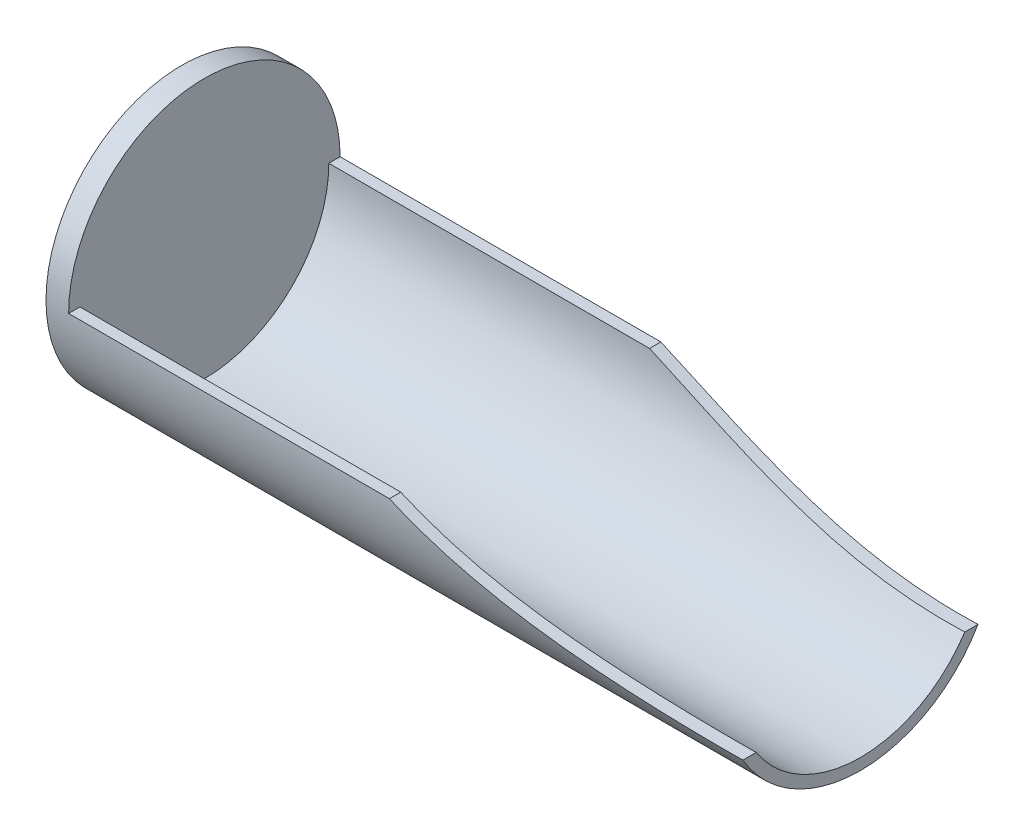
SolidWorks part; units mm, degrees
ref_plane "Front Plane" through (0, 0, 0) normal (0, 0, 1) x (1, 0, 0)
ref_plane "Top Plane" through (0, 0, 0) normal (0, 1, 0) x (1, 0, 0)
ref_plane "Right Plane" through (0, 0, 0) normal (1, 0, 0) x (0, 0, -1)
sketch "Sketch1" plane through (0, 0, 0) normal (1, 0, 0) x (0, 0, -1)
  circle A0 centre (0, 0) radius 120
  dimension "D1" = 240
extrude "Boss-Extrude1" add sketch "Sketch1" along normal blind 600
sketch "Sketch2" plane through (600, 0, 0) normal (1, 0, 0) x (0, 0, -1)
  line L2 (-110, 0) -> (-120, 0)
  line L3 (110, 0) -> (120, 0)
  arc A0 (-110, 0) -> (110, 0) centre (0, 0) ccw
  circle A1 centre (0, 0) radius 120 construction
  arc A2 (120, 0) -> (-120, 0) centre (0, 0) ccw
  dimension "D1" = 110
extrude "Cut-Extrude1" cut sketch "Sketch2" against normal blind 580
sketch "Sketch5" plane through (0, 0, 0) normal (0, 0, 1) x (1, 0, 0)
  line L0 (20, 0) -> (600, 0) construction
  line L1 (600, -120) -> (600, 0) construction
  line L2 (303.5799, 0) -> (600, 0)
  line L3 (600, 0) -> (600, -60)
  spline S0 degree 2 poles (303.5799, 0) (445.5694, -63.3403) (600, -60) knots 0 0 0 1 1 1
extrude "Cut-Extrude3" cut sketch "Sketch5" against normal through all both and the other way through all
